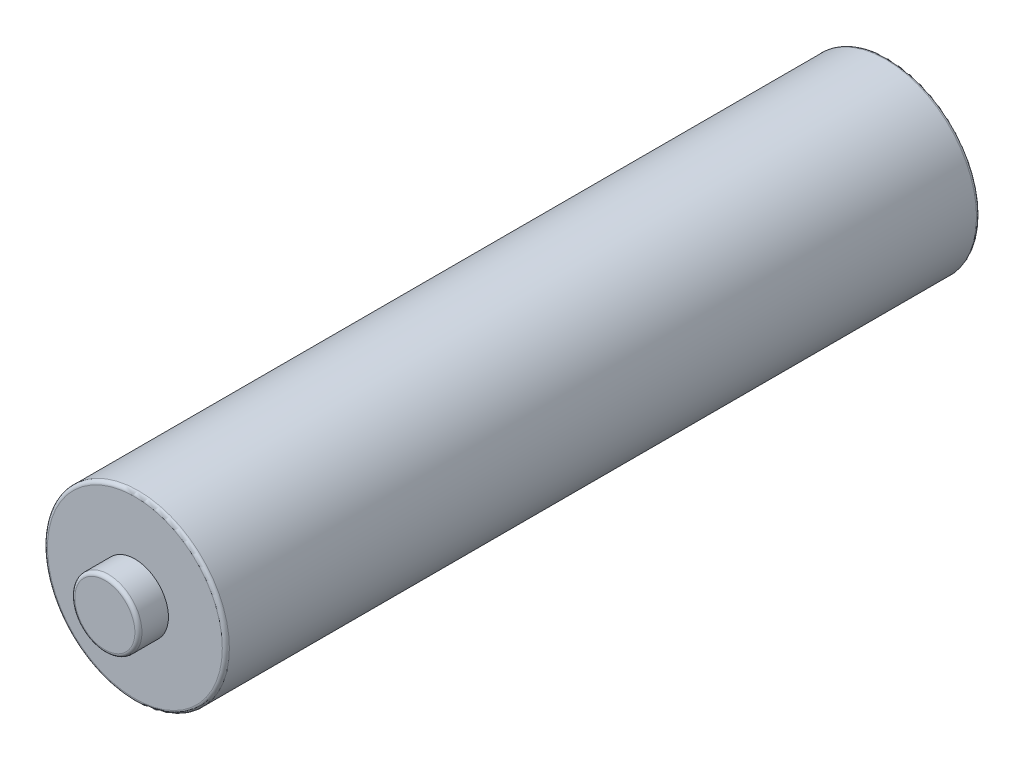
SolidWorks part; units mm, degrees
ref_plane "Přední rovina" through (0, 0, 0) normal (0, 0, 1) x (1, 0, 0)
ref_plane "Horní rovina" through (0, 0, 0) normal (0, 1, 0) x (1, 0, 0)
ref_plane "Pravá rovina" through (0, 0, 0) normal (1, 0, 0) x (0, 0, -1)
sketch "Skica1" plane through (0, 0, 0) normal (0, 0, 1) x (1, 0, 0)
  circle A0 centre (0, 0) radius 5.15
  dimension "D1" = 10.3
extrude "Přidat vysunutím1" add sketch "Skica1" along normal blind 42.7
sketch "Skica2" plane through (0, 0, 42.7) normal (0, 0, 1) x (1, 0, 0)
  circle A0 centre (0, 0) radius 1.9
  dimension "D1" = 3.8
extrude "Přidat vysunutím2" add sketch "Skica2" along normal blind 1.7
fillet "Zaoblit1" radius 0.2 1 edges at (1.9, 0, 44.4)
fillet "Zaoblit2" radius 0.2 2 edges at (5.15, 0, 0) (5.15, 0, 42.7)
